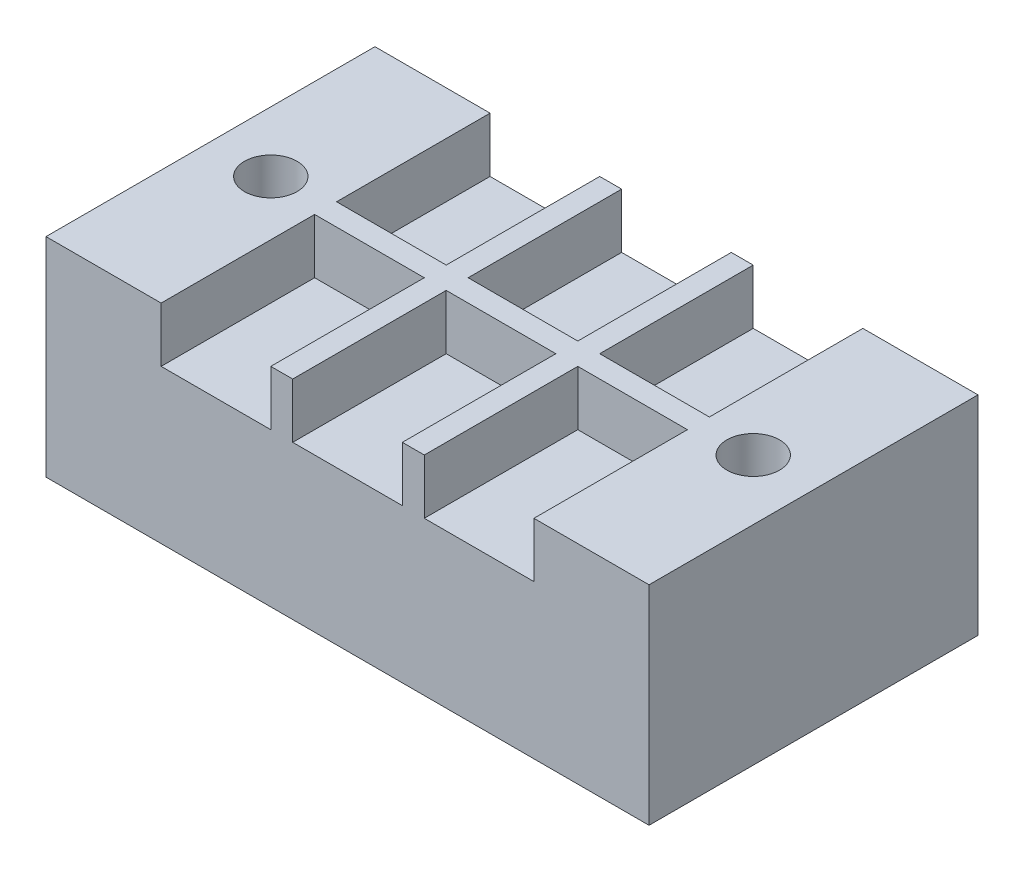
SolidWorks part; units mm, degrees
ref_plane "前视基准面" through (0, 0, 0) normal (0, 0, 1) x (1, 0, 0)
ref_plane "上视基准面" through (0, 0, 0) normal (0, 1, 0) x (1, 0, 0)
ref_plane "右视基准面" through (0, 0, 0) normal (1, 0, 0) x (0, 0, -1)
sketch "草图1" plane through (0, 0, 0) normal (0, 1, 0) x (1, 0, 0)
  line L1 (27.5, -15) -> (-27.5, -15)
  line L2 (27.5, -15) -> (27.5, 15)
  line L3 (27.5, 15) -> (-27.5, 15)
  line L4 (-27.5, -15) -> (-27.5, 15)
  line L5 (27.5, -15) -> (-27.5, 15) construction
  line L6 (27.5, 15) -> (-27.5, -15) construction
  point P0 (0, 0)
  dimension "D1" = 55
  dimension "D2" = 30
extrude "凸台-拉伸1" add sketch "草图1" along normal blind 19 contours L3 L4 L1 L2
sketch "草图2" plane through (0, 19, 0) normal (0, 1, 0) x (1, 0, 0)
  line L0 (0, 0) -> (0, 8.3631) construction
  circle A0 centre (-22, 0) radius 2.4
  circle A1 centre (22, 0) radius 2.4
  dimension "D1" = 4.8
  dimension "D2" = 22
extrude "切除-拉伸1" cut sketch "草图2" against normal through all
sketch "草图3" plane through (0, 19, 0) normal (0, 1, 0) x (1, 0, 0)
  line L0 (27.5, 15) -> (-27.5, 15) construction
  line L1 (-17, 15) -> (-7, 15)
  line L2 (-17, 15) -> (-17, 1)
  line L3 (-17, 1) -> (-7, 1)
  line L4 (-7, 15) -> (-7, 1)
  line L5 (0, 0) -> (0, 16.9944) construction
  line L6 (-5, 15) -> (5, 15)
  line L7 (-5, 15) -> (-5, 1)
  line L8 (-5, 1) -> (5, 1)
  line L9 (5, 15) -> (5, 1)
  line L10 (7, 15) -> (17, 15)
  line L11 (7, 15) -> (7, 1)
  line L12 (7, 1) -> (17, 1)
  line L13 (17, 15) -> (17, 1)
  line L14 (0, 0) -> (33.7118, 0) construction
  line L15 (17, -15) -> (17, -1)
  line L16 (7, -1) -> (17, -1)
  line L17 (7, -15) -> (7, -1)
  line L18 (7, -15) -> (17, -15)
  line L19 (5, -15) -> (5, -1)
  line L20 (-5, -1) -> (5, -1)
  line L21 (-5, -15) -> (-5, -1)
  line L22 (-5, -15) -> (5, -15)
  line L23 (-7, -15) -> (-7, -1)
  line L24 (-17, -1) -> (-7, -1)
  line L25 (-17, -15) -> (-17, -1)
  line L26 (-17, -15) -> (-7, -15)
  dimension "D1" = 10
  dimension "D2" = 10
  dimension "D3" = 2
  dimension "D4" = 1
extrude "切除-拉伸2" cut sketch "草图3" against normal blind 5
